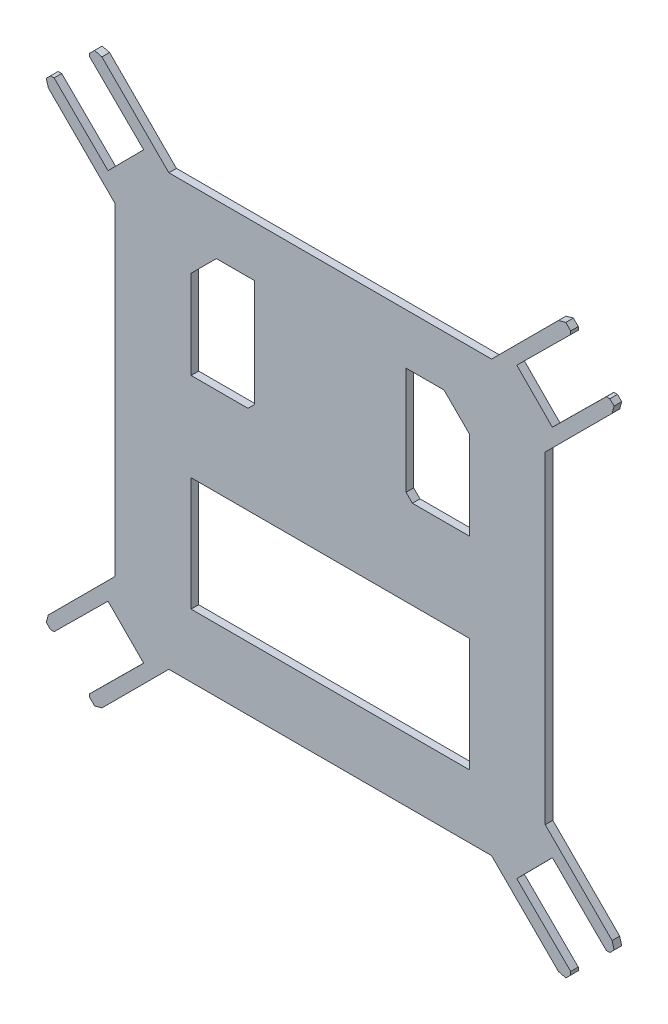
SolidWorks part; units mm, degrees
ref_plane "Front Plane" through (0, 0, 0) normal (0, 0, 1) x (1, 0, 0)
ref_plane "Top Plane" through (0, 0, 0) normal (0, 1, 0) x (1, 0, 0)
ref_plane "Right Plane" through (0, 0, 0) normal (1, 0, 0) x (0, 0, -1)
sketch "Sketch1" plane through (0, 0, 0) normal (0, 0, 1) x (1, 0, 0)
  line L0 (-25.5585, 109.7968) -> (-24.1443, 109.7968)
  line L1 (21.2132, -70) -> (148.7868, -70)
  line L2 (0, -48.7868) -> (0, 78.7868)
  line L3 (21.2132, 100) -> (148.7868, 100)
  line L4 (170, -48.7868) -> (170, 78.7868)
  line L5 (-24.1443, 109.7968) -> (-2.8287, 88.6865)
  line L7 (21.2132, 100) -> (-5.234, 126.4472)
  line L8 (-8.1317, 127.2236) -> (-10.0706, 125.2848)
  line L9 (-26.4472, 105.234) -> (0, 78.7868)
  line L10 (197.2236, -78.1317) -> (195.5585, -79.7968)
  line L11 (170, -48.7868) -> (196.4472, -75.2339)
  line L13 (175.2339, -96.4472) -> (148.7868, -70)
  line L15 (178.1317, 127.2236) -> (180.0706, 125.2848)
  line L16 (148.7868, 100) -> (175.2339, 126.4472)
  line L18 (196.4472, 105.234) -> (170, 78.7868)
  line L19 (0, -48.7868) -> (-26.4472, -75.2339)
  line L21 (-5.234, -96.4472) -> (21.2132, -70)
  line L22 (-27.2236, -78.1317) -> (-25.5585, -79.7968)
  line L23 (-2.8287, 88.6865) -> (11.245, 102.8971)
  line L24 (11.245, 102.8971) -> (-10.0706, 124.0074)
  line L25 (-27.2236, 108.1317) -> (-26.4472, 105.234)
  line L26 (-10.0706, 124.0074) -> (-10.0706, 125.2848)
  line L27 (-8.1317, 127.2236) -> (-5.234, 126.4472)
  line L29 (-25.5585, 109.7968) -> (-27.2236, 108.1317)
  line L30 (-8.1317, -97.2236) -> (-5.234, -96.4472)
  line L31 (-8.1317, -97.2236) -> (-10.0706, -95.2848)
  line L32 (-10.0706, -94.0074) -> (-10.0706, -95.2848)
  line L33 (11.245, -72.8971) -> (-10.0706, -94.0074)
  line L34 (-2.8287, -58.6865) -> (11.245, -72.8971)
  line L35 (-27.2236, -78.1317) -> (-26.4472, -75.2339)
  line L36 (-25.5585, -79.7968) -> (-24.1443, -79.7968)
  line L37 (-24.1443, -79.7968) -> (-2.8287, -58.6865)
  line L38 (-10.0706, -95.2848) -> (-8.1317, -97.2236)
  line L39 (195.5585, 109.7968) -> (194.1443, 109.7968)
  line L40 (195.5585, 109.7968) -> (197.2236, 108.1317)
  line L41 (197.2236, 108.1317) -> (196.4472, 105.234)
  line L42 (194.1443, 109.7968) -> (172.8287, 88.6865)
  line L43 (178.1317, 127.2236) -> (175.2339, 126.4472)
  line L44 (180.0706, 124.0074) -> (180.0706, 125.2848)
  line L45 (158.755, 102.8971) -> (180.0706, 124.0074)
  line L46 (195.5585, 109.7968) -> (197.2236, 108.1317)
  line L47 (172.8287, 88.6865) -> (158.755, 102.8971)
  line L48 (178.1317, -97.2236) -> (175.2339, -96.4472)
  line L49 (178.1317, -97.2236) -> (180.0706, -95.2848)
  line L50 (180.0706, -94.0074) -> (180.0706, -95.2848)
  line L51 (197.2236, -78.1317) -> (196.4472, -75.2339)
  line L52 (195.5585, -79.7968) -> (197.2236, -78.1317)
  line L53 (195.5585, -79.7968) -> (194.1443, -79.7968)
  line L54 (194.1443, -79.7968) -> (172.8287, -58.6865)
  line L55 (172.8287, -58.6865) -> (158.755, -72.8971)
  line L56 (158.755, -72.8971) -> (180.0706, -94.0074)
  line L57 (180.0706, -95.2848) -> (178.1317, -97.2236)
  dimension "D1" = 5
  dimension "D2" = 5
  dimension "D3" = 127.5736
  dimension "D4" = 30
  dimension "D5" = 30
  dimension "D6" = 127.5736
  dimension "D7" = 1
  dimension "D8" = 45
  dimension "D9" = 30
  dimension "D10" = 30
  dimension "D11" = 127.5736
  dimension "D12" = 127.5736
extrude "Boss-Extrude1" add sketch "Sketch1" along normal blind 3 contours L56 L55 L54 L53 L10 L51 L11 L4 L18 L41 L40 L39 L42 L47 L45 L44 L15 L43 L16 L3 L7 L27 L8 L26 L24 L23 L5 L0 L29 L25 L9 L2 L19 L35 L22 L36 L37 L34 L33 L32 L31 L30 L21 L1 L13 L48 L49 L50
sketch "Sketch2" plane through (0, 0, 3) normal (0, 0, 1) x (1, 0, 0)
  line L0 (85, 100) -> (85, -70) construction
  line L1 (21.2132, 100) -> (148.7868, 100) construction
  line L2 (21.2132, -70) -> (148.7868, -70) construction
  line L3 (0, 15) -> (170, 15) construction
  line L4 (0, -48.7868) -> (0, 78.7868) construction
  line L5 (170, -48.7868) -> (170, 78.7868) construction
  line L6 (30, 70) -> (40, 80)
  line L7 (40, 80) -> (55, 80)
  line L8 (30, 70) -> (30, 35)
  line L9 (30, 35) -> (52.5, 35)
  line L10 (55, 80) -> (55, 37.5)
  line L11 (52.5, 35) -> (55, 37.5)
  line L24 (140, 35) -> (117.5, 35)
  line L25 (117.5, 35) -> (115, 37.5)
  line L26 (115, 80) -> (115, 37.5)
  line L27 (130, 80) -> (115, 80)
  line L28 (140, 70) -> (130, 80)
  line L29 (140, 70) -> (140, 35)
  line L31 (30, 0) -> (140, 0)
  line L32 (30, 0) -> (30, -45)
  line L33 (30, -45) -> (140, -45)
  line L34 (140, 0) -> (140, -45)
  point P12 (30, 80)
  point P13 (55, 35)
  dimension "D5" = 15
  dimension "D1" = 30
  dimension "D2" = 30
  dimension "D3" = 20
  dimension "D4" = 20
  dimension "D6" = 25
extrude "Cut-Extrude1" cut sketch "Sketch2" against normal blind 10
